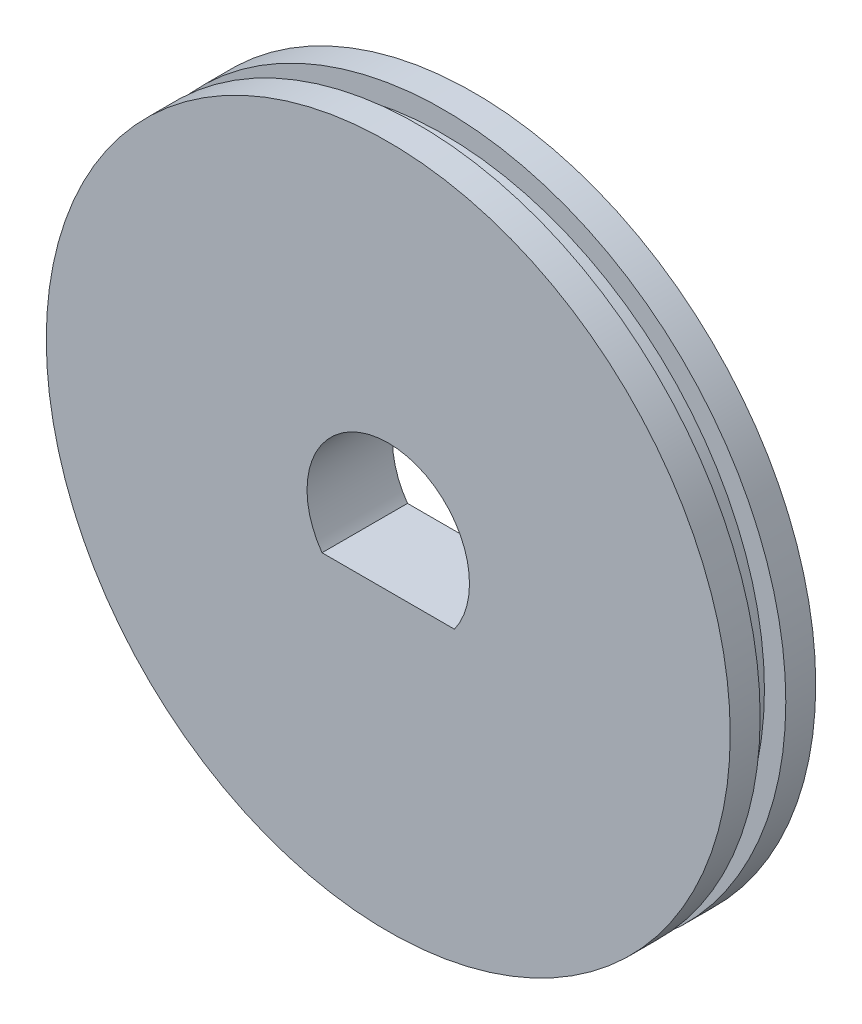
SolidWorks part; units mm, degrees
ref_plane "Front Plane" through (0, 0, 0) normal (0, 0, 1) x (1, 0, 0)
ref_plane "Top Plane" through (0, 0, 0) normal (0, 1, 0) x (1, 0, 0)
ref_plane "Right Plane" through (0, 0, 0) normal (1, 0, 0) x (0, 0, -1)
sketch "Sketch1" plane through (0, 0, 0) normal (0, 0, 1) x (1, 0, 0)
  line L0 (-1.5492, -1.1) -> (1.5492, -1.1)
  arc A0 (1.5492, -1.1) -> (-1.5492, -1.1) centre (0, 0) ccw
  circle A1 centre (0, 0) radius 8
  dimension "D1" = 16
extrude "Boss-Extrude2" add sketch "Sketch1" along normal blind 2
sketch "Sketch2" plane through (0, 0, 0) normal (0, 1, 0) x (1, 0, 0)
  line L0 (-8, 0) -> (-8, -0.7) construction
  line L1 (-8, 0) -> (-8, -2) construction
  line L2 (-8, -2) -> (-8, -1.3) construction
  line L3 (-8, -0.7) -> (-7.5, -0.7)
  line L7 (-8, -0.7) -> (-8, -1.3)
  line L8 (-7.5, -0.7) -> (-7.5, -1.3)
  line L9 (-7.5, -1.3) -> (-8, -1.3)
  dimension "D1" = 0.5
  dimension "D2" = 0.7
revolve "Cut-Revolve1" cut sketch "Sketch2" angle 360 about axis through (0, 0, 2) along (0, 0, -1)
sketch "Sketch3" plane through (0, 0, 0) normal (0, 0, 1) x (1, 0, 0)
  line L0 (-1000, 0) -> (49000, 0) construction
  line L1 (0, 0) -> (3.873, -7) construction
  line L2 (0, 0) -> (0, -8) construction
  line L3 (0, 0) -> (-3.873, -7) construction
  line L4 (-3.873, -7) -> (3.873, -7)
  line L6 (0, 0) -> (0, -5.5) construction
  line L7 (-5.5, -5.5) -> (-2.5, -5.5) construction
  line L8 (-5.5, -5.5) -> (5.5, -5.5) construction
  line L9 (-2.5, -5.5) -> (-5.5, -2.5) construction
  line L10 (0, -5.5) -> (0, 6.5) construction
  line L11 (0, -8.5) -> (0, 7.5) construction
  line L12 (-5.5, 6.5) -> (5.5, 6.5)
  circle A0 centre (0, 0) radius 8 construction
  arc A2 (-3.873, -7) -> (3.873, -7) centre (0, 0) ccw
  point P15 (0, -5.5)
  point P22 (0, 6.5)
  dimension "D1" = 1
  dimension "D2" = 3
  dimension "D3" = 11
